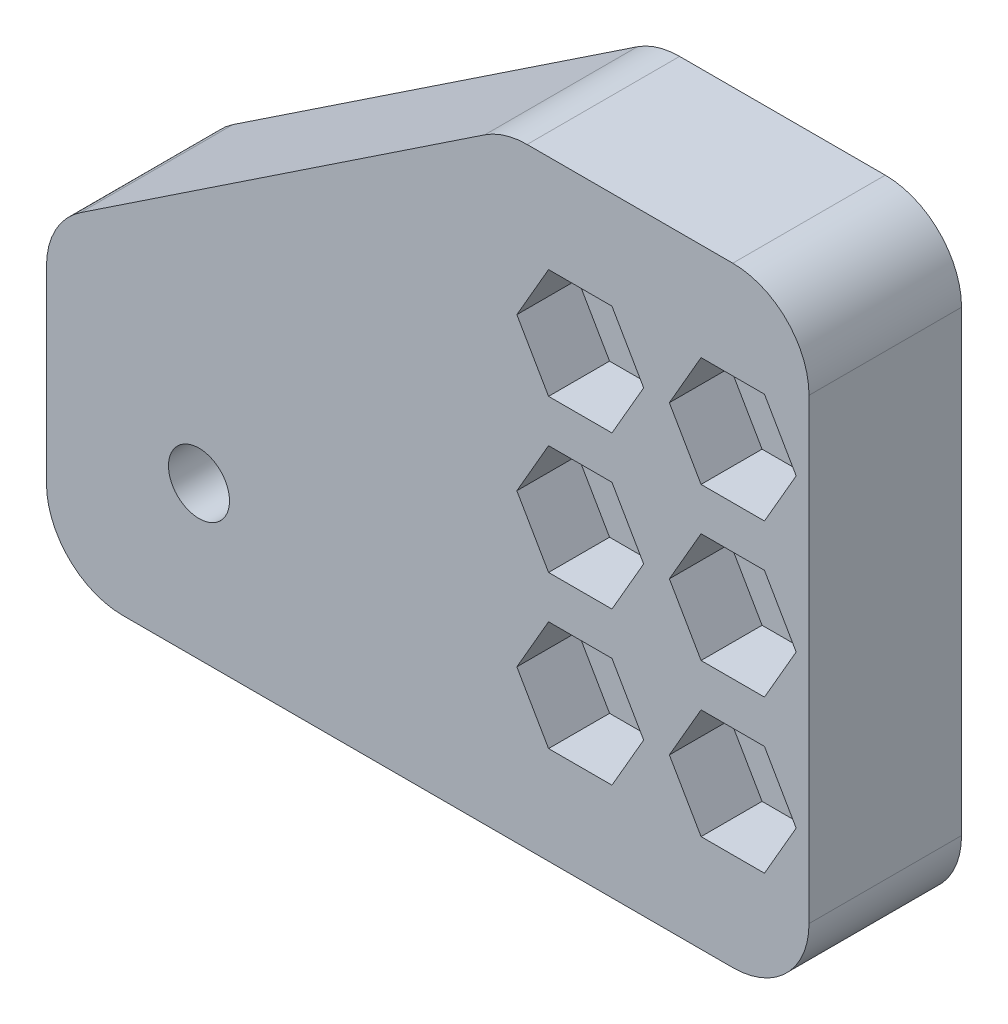
SolidWorks part; units mm, degrees
ref_plane "Front Plane" through (0, 0, 0) normal (0, 0, 1) x (1, 0, 0)
ref_plane "Top Plane" through (0, 0, 0) normal (0, 1, 0) x (1, 0, 0)
ref_plane "Right Plane" through (0, 0, 0) normal (1, 0, 0) x (0, 0, -1)
sketch "Sketch1" plane through (0, 0, 0) normal (0, 0, 1) x (1, 0, 0)
  line L0 (-6.35, 38.1) -> (-44.45, 12.7)
  line L1 (-6.35, -12.7) -> (19.05, -12.7)
  line L3 (-6.35, 38.1) -> (19.05, 38.1)
  line L4 (19.05, -12.7) -> (19.05, 38.1)
  line L5 (-44.45, 12.7) -> (-44.45, -12.7)
  line L6 (-44.45, -12.7) -> (-6.35, -12.7)
  circle A0 centre (0, 0) radius 2.286
  circle A1 centre (-31.75, 0) radius 2.54
  circle A2 centre (12.7, 0) radius 2.286
  circle A3 centre (12.7, 12.7) radius 2.286
  circle A4 centre (12.7, 25.4) radius 2.286
  circle A5 centre (0, 12.7) radius 2.286
  circle A6 centre (0, 25.4) radius 2.286
  dimension "D7" = 4.572
  dimension "D8" = 5.08
  dimension "D1" = 12.7
  dimension "D2" = 12.7
  dimension "D3" = 38.1
  dimension "D4" = 25.4
  dimension "D5" = 25.4
  dimension "D6" = 6.35
  dimension "D11" = 50.8
  dimension "D9" = 2
  dimension "D10" = 3
extrude "Boss-Extrude1" add sketch "Sketch1" along normal blind 12.7
fillet "Fillet1" radius 6.35 5 edges at (-44.45, 12.7, 6.35) (-6.35, 38.1, 6.35) (19.05, 38.1, 6.35) (19.05, -12.7, 6.35) (-44.45, -12.7, 6.35)
ref_plane "Plane1" through (-5.08, 0, 0) normal (1, 0, 0) x (0, 0, -1)
sketch "Sketch2" plane through (-5.08, 0, 0) normal (1, 0, 0) x (0, 0, -1)
  line L0 (0, 3.81) -> (-11.5604, -12.7)
  line L1 (0, 9.3016) -> (0, -6.35) construction
  line L2 (-12.7, -12.7) -> (0, -12.7) construction
  line L3 (-11.5604, -12.7) -> (0, -12.7)
  line L4 (0, -12.7) -> (0, 3.81)
  line L5 (-18.353, -23.4237) -> (0.581, 3.6168) construction
  dimension "D1" = 16.51
extrude "Cut-Extrude1" cut sketch "Sketch2" against normal blind 8.89
fillet "Fillet2" radius 2.54 4 edges at (-13.97, -4.445, 0) (-13.97, -12.7, 5.7802) (-5.08, -12.7, 5.7802) (-5.08, -4.445, 0)
sketch "Sketch3" plane through (0, 0, 12.7) normal (0, 0, 1) x (1, 0, 0)
  line L0 (17.9793, 0) -> (15.3396, 4.572)
  line L1 (5.2793, 0) -> (2.6396, 4.572)
  line L2 (2.6396, 4.572) -> (-2.6396, 4.572)
  line L3 (-2.6396, 4.572) -> (-5.2793, 0)
  line L4 (-5.2793, 0) -> (-2.6396, -4.572)
  line L5 (-2.6396, -4.572) -> (2.6396, -4.572)
  line L6 (2.6396, -4.572) -> (5.2793, 0)
  line L7 (15.3396, 4.572) -> (10.0604, 4.572)
  line L8 (10.0604, 4.572) -> (7.4207, 0)
  line L9 (7.4207, 0) -> (10.0604, -4.572)
  line L10 (10.0604, -4.572) -> (15.3396, -4.572)
  line L11 (15.3396, -4.572) -> (17.9793, 0)
  line L12 (17.9793, 12.7) -> (15.3396, 17.272)
  line L13 (15.3396, 17.272) -> (10.0604, 17.272)
  line L14 (10.0604, 17.272) -> (7.4207, 12.7)
  line L15 (7.4207, 12.7) -> (10.0604, 8.128)
  line L16 (10.0604, 8.128) -> (15.3396, 8.128)
  line L17 (15.3396, 8.128) -> (17.9793, 12.7)
  line L18 (17.9793, 25.4) -> (15.3396, 29.972)
  line L19 (15.3396, 29.972) -> (10.0604, 29.972)
  line L20 (10.0604, 29.972) -> (7.4207, 25.4)
  line L21 (7.4207, 25.4) -> (10.0604, 20.828)
  line L22 (10.0604, 20.828) -> (15.3396, 20.828)
  line L23 (15.3396, 20.828) -> (17.9793, 25.4)
  line L24 (5.2793, 12.7) -> (2.6396, 17.272)
  line L25 (2.6396, 17.272) -> (-2.6396, 17.272)
  line L26 (-2.6396, 17.272) -> (-5.2793, 12.7)
  line L27 (-5.2793, 12.7) -> (-2.6396, 8.128)
  line L28 (-2.6396, 8.128) -> (2.6396, 8.128)
  line L29 (2.6396, 8.128) -> (5.2793, 12.7)
  line L30 (5.2793, 25.4) -> (2.6396, 29.972)
  line L31 (2.6396, 29.972) -> (-2.6396, 29.972)
  line L32 (-2.6396, 29.972) -> (-5.2793, 25.4)
  line L33 (-5.2793, 25.4) -> (-2.6396, 20.828)
  line L34 (-2.6396, 20.828) -> (2.6396, 20.828)
  line L35 (2.6396, 20.828) -> (5.2793, 25.4)
  circle A0 centre (0, 0) radius 4.572 construction
  circle A1 centre (12.7, 0) radius 4.572 construction
  circle A2 centre (12.7, 12.7) radius 4.572 construction
  circle A3 centre (12.7, 25.4) radius 4.572 construction
  circle A4 centre (0, 12.7) radius 4.572 construction
  circle A5 centre (0, 25.4) radius 4.572 construction
  dimension "D1" = 9.144
  dimension "D2" = 2
  dimension "D3" = 3
extrude "Cut-Extrude2" cut sketch "Sketch3" against normal blind 5.08
